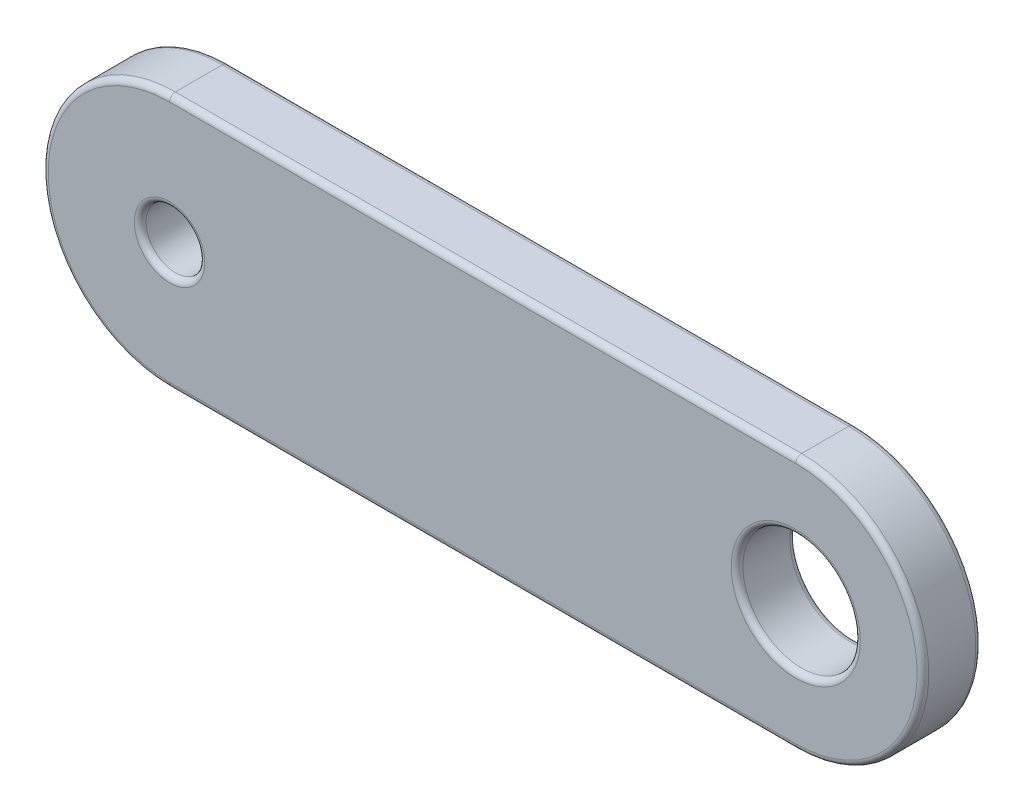
SolidWorks part; units mm, degrees
ref_plane "Front Plane" through (0, 0, 0) normal (0, 0, 1) x (1, 0, 0)
ref_plane "Top Plane" through (0, 0, 0) normal (0, 1, 0) x (1, 0, 0)
ref_plane "Right Plane" through (0, 0, 0) normal (1, 0, 0) x (0, 0, -1)
sketch "Sketch1" plane through (0, 0, 0) normal (0, 0, 1) x (1, 0, 0)
  line L0 (-8, 0) -> (8, 0) construction
  line L1 (-8, 3.25) -> (8, 3.25)
  line L2 (-8, -3.25) -> (8, -3.25)
  arc A0 (-8, 3.25) -> (-8, -3.25) centre (-8, 0) ccw
  arc A1 (8, -3.25) -> (8, 3.25) centre (8, 0) ccw
  circle A2 centre (-8, 0) radius 0.75
  circle A3 centre (8, 0) radius 1.5
  point P2 (0, 0)
  dimension "D3" = 1.5
  dimension "D4" = 3
  dimension "D1" = 16
  dimension "D2" = 6.5
extrude "Boss-Extrude1" add sketch "Sketch1" along normal mid plane 1.5
fillet "Fillet1" radius 0.15 12 edges at (9.5, 0, -0.75) (9.5, 0, 0.75) (-7.25, 0, -0.75) (-7.25, 0, 0.75) (-11.25, 0, -0.75) (0, -3.25, -0.75) (11.25, 0, -0.75) (0, 3.25, -0.75) (-11.25, 0, 0.75) (0, -3.25, 0.75) (11.25, 0, 0.75) (0, 3.25, 0.75)
